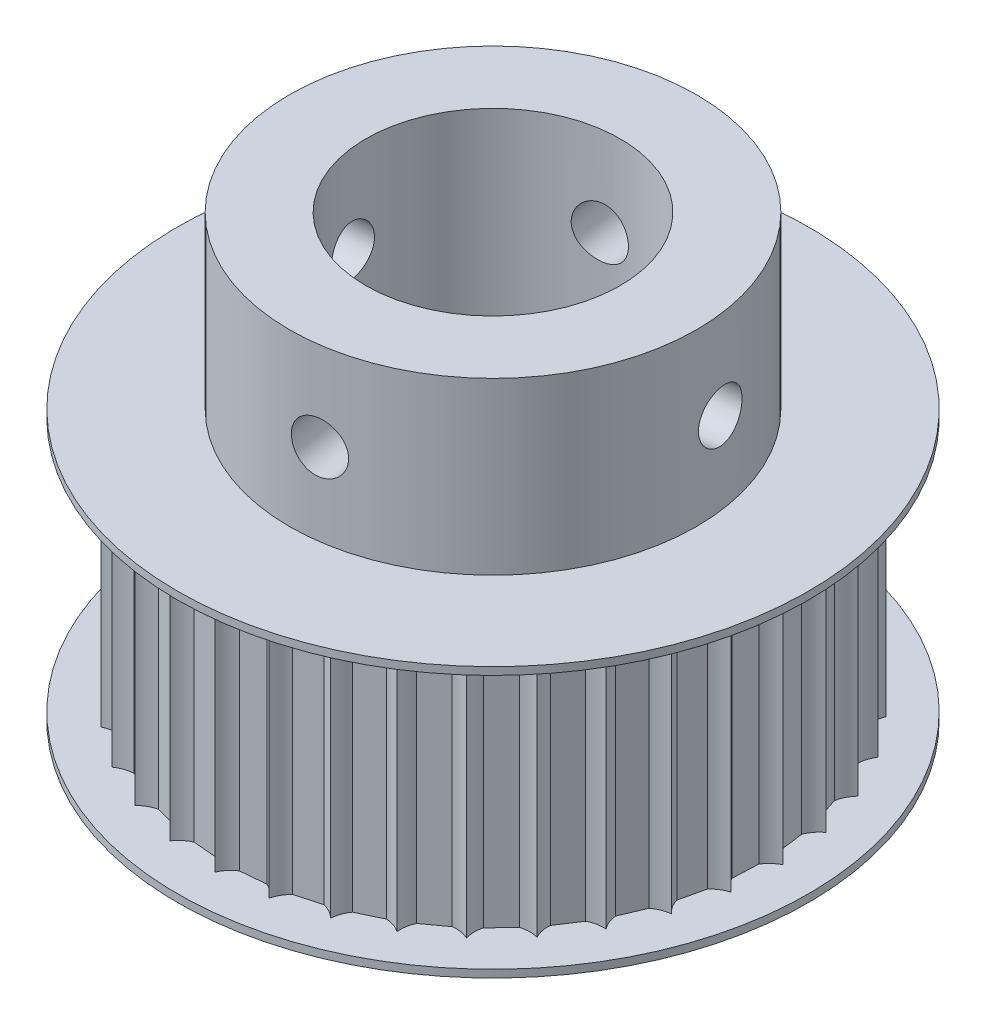
SolidWorks part; units mm, degrees
ref_plane "Front Plane" through (0, 0, 0) normal (0, 0, 1) x (1, 0, 0)
ref_plane "Top Plane" through (0, 0, 0) normal (0, 1, 0) x (1, 0, 0)
ref_plane "Right Plane" through (0, 0, 0) normal (1, 0, 0) x (0, 0, -1)
sketch "Sketch1" plane through (0, 0, 0) normal (0, 0, 1) x (1, 0, 0)
  line L0 (0, 0) -> (0, 9.78) construction
  line L1 (4, 0) -> (14, 0)
  line L2 (14, 0) -> (14, 10)
  line L3 (14, 10) -> (8, 10)
  line L4 (8, 10) -> (8, 17)
  line L5 (8, 17) -> (4, 17)
  line L6 (4, 17) -> (4, 0)
  dimension "D1" = 4
  dimension "D2" = 10
  dimension "D3" = 17
  dimension "D4" = 4
  dimension "D5" = 10
revolve "Revolve1" add sketch "Sketch1" angle 360 about L0
sketch "Sketch2" plane through (0, 10, 0) normal (0, 1, 0) x (1, 0, 0)
  line L0 (0, 0) -> (0, 12.4) construction
  line L1 (0, 0) -> (4.8263, 11.4725) construction
  line L2 (-0.5, 10.4) -> (0.5, 10.4)
  line L6 (-1.4, 12.0142) -> (-1.4, 14.3643)
  line L7 (-1.4, 14.3643) -> (1.4, 14.3643)
  line L8 (1.4, 14.3643) -> (1.4, 12.0142)
  arc A0 (0.5, 10.4) -> (1.0965, 11.7108) centre (-0.0755, 11.453) ccw
  arc A3 (-0.5, 10.4) -> (-1.0965, 11.7108) centre (0.0755, 11.453) cw
  arc A4 (1.0965, 11.7108) -> (1.4, 12.0142) centre (1.4, 11.7108) cw
  arc A5 (-1.0965, 11.7108) -> (-1.4, 12.0142) centre (-1.4, 11.7108) ccw
  point P3 (0, 10.4)
  point P8 (0, 10.4)
  dimension "D6" = 1.2
  dimension "D1" = 12.4
  dimension "D2" = 12.4464
  dimension "D3" = 2
  dimension "D4" = 1
  dimension "D5" = 2.8
extrude "Cut-Extrude2" cut sketch "Sketch2" against normal through all contours L6 L7 L8 A4 A0 L2 A3 A5
pattern_circular "CirPattern3" count 35 over 360 about axis through (0, 0, 0) along (0, 1, 0) of "Cut-Extrude2"
sketch "Sketch3" plane through (0, 10, 0) normal (0, 1, 0) x (1, 0, 0)
  circle A0 centre (0, 0) radius 12.4
  dimension "D1" = 24.8
extrude "Boss-Extrude1" add sketch "Sketch3" along normal blind 0.3
sketch "Sketch4" plane through (0, 0, 0) normal (0, -1, 0) x (1, 0, 0)
  circle A0 centre (0, 0) radius 12.4
extrude "Boss-Extrude2" add sketch "Sketch4" along normal blind 0.3
sketch "Sketch5" plane through (0, -0.3, 0) normal (0, -1, 0) x (1, 0, 0)
  circle A0 centre (0, 0) radius 4
  dimension "D1" = 8
extrude "Cut-Extrude3" cut sketch "Sketch5" against normal through all
sketch "Sketch7" plane through (10.3059, 0, -1.396) normal (0.9909, 0, -0.1342) x (-0.1342, 0, -0.9909)
  line L0 (4, 17) -> (-4, 17) construction
  circle A0 centre (0, 13.5) radius 1
  point P0 (0, 13.5)
  dimension "D2" = 2
  dimension "D1" = 3.5
extrude "Cut-Extrude4" cut sketch "Sketch7" against normal through all
pattern_circular "CirPattern4" count 4 over 360 about axis through (0, 0, 0) along (0, -1, 0) of "Cut-Extrude4"
sketch "Sketch8" plane through (0, 17, 0) normal (0, 1, 0) x (1, 0, 0)
  circle A0 centre (0, 0) radius 5
  dimension "D1" = 10
extrude "Cut-Extrude5" cut sketch "Sketch8" against normal through all
